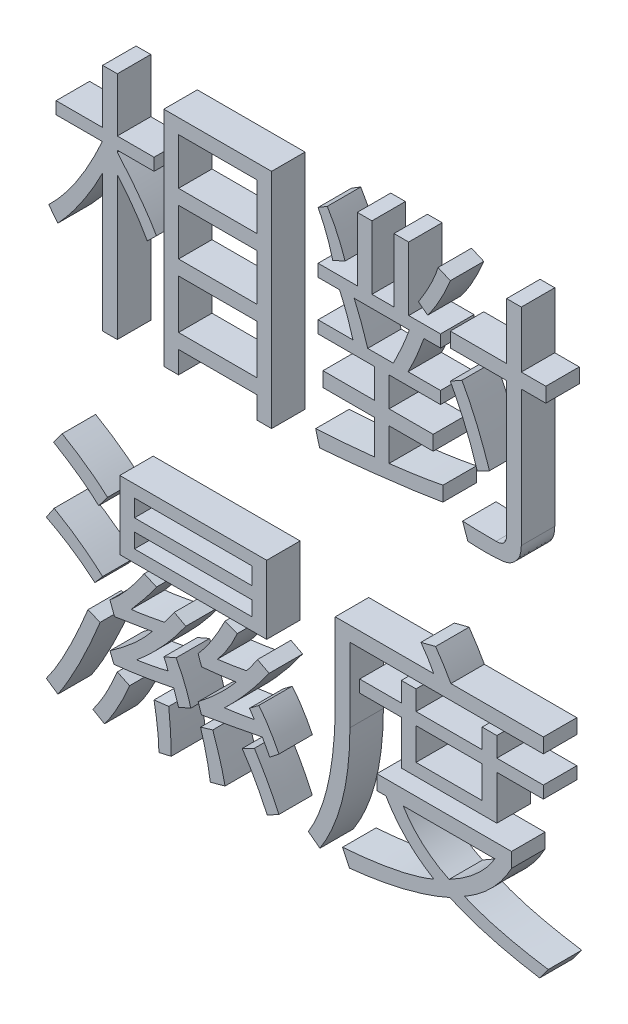
SolidWorks part; units mm, degrees
ref_plane "前基準面" through (0, 0, 0) normal (0, 0, 1) x (1, 0, 0)
ref_plane "上基準面" through (0, 0, 0) normal (0, 1, 0) x (1, 0, 0)
ref_plane "右基準面" through (0, 0, 0) normal (1, 0, 0) x (0, 0, -1)
sketch "草圖2" plane through (0, 0, 0) normal (0, 0, 1) x (1, 0, 0)
  text T0 "相對\r\n濕度" font "微軟正黑體" height 18
extrude "填料-伸長1" add sketch "草圖2" along normal blind 3
